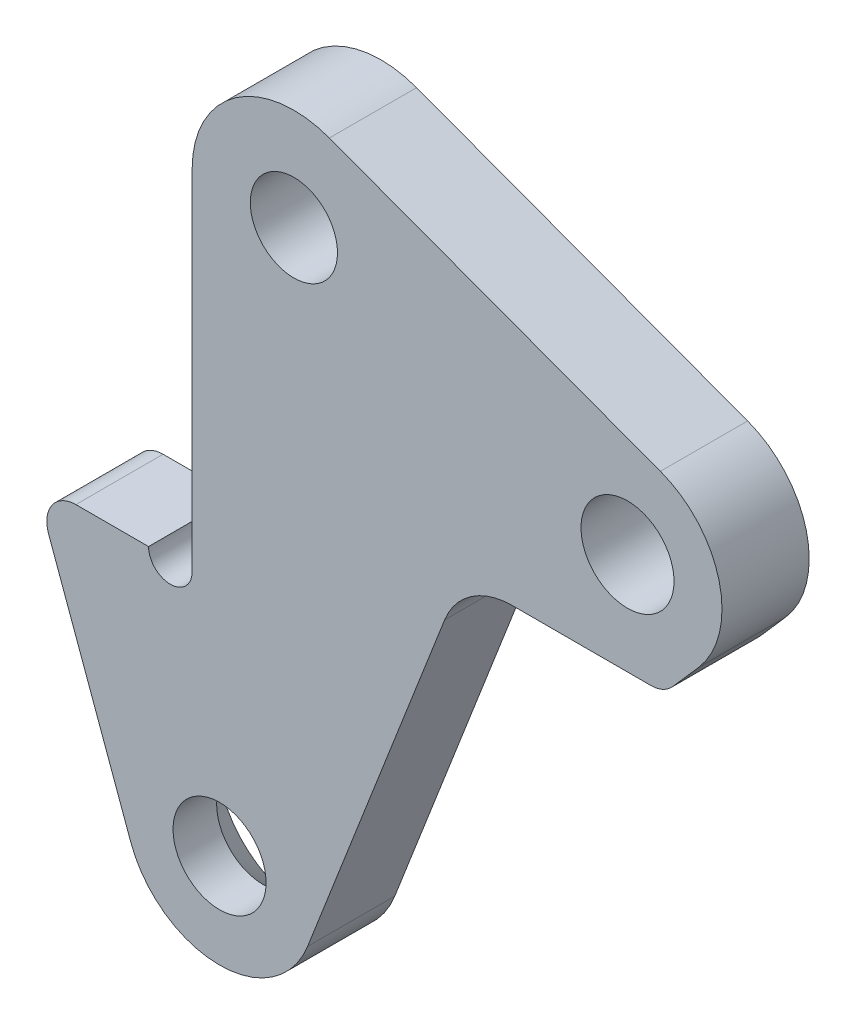
SolidWorks part; units mm, degrees
ref_plane "前视基准面" through (0, 0, 0) normal (0, 0, 1) x (1, 0, 0)
ref_plane "上视基准面" through (0, 0, 0) normal (0, 1, 0) x (1, 0, 0)
ref_plane "右视基准面" through (0, 0, 0) normal (1, 0, 0) x (0, 0, -1)
sketch "草图1" plane through (0, 0, 0) normal (0, 0, 1) x (1, 0, 0)
  line L0 (-7.5, -12) -> (-3.5, -12)
  line L1 (-3.5, -12) -> (-3.5, 0)
  line L2 (-8.4397, -13.342) -> (-5.6118, -21.1116)
  line L3 (1.2196, 3.2806) -> (12.6097, -0.9537)
  line L4 (-0.1146, -22.1432) -> (13.9204, -6.1432)
  line L5 (-8.4373, -12.6515) -> (-3.2806, 1.2196) construction
  circle A0 centre (0, 0) radius 1.5
  arc A1 (-5.6118, -21.1116) -> (-0.1146, -22.1432) centre (-2.5578, -20) ccw
  circle A2 centre (-2.5578, -20) radius 1.6
  arc A3 (-7.5, -12) -> (-8.4397, -13.342) centre (-7.5, -13) ccw
  arc A4 (-3.5, 0) -> (1.2196, 3.2806) centre (0, 0) cw
  circle A5 centre (11.4772, -4) radius 1.6
  arc A6 (13.9204, -6.1432) -> (12.6097, -0.9537) centre (11.4772, -4) ccw
  point P18 (-8.9281, -12)
  dimension "D2" = 3
  dimension "D4" = 3.2
  dimension "D5" = 3.25
  dimension "D7" = 1
  dimension "D10" = 3.25
  dimension "D11" = 3.2
  dimension "D3" = 70
  dimension "D6" = 8
  dimension "D1" = 4
  dimension "D8" = 20
  dimension "D9" = 3.5
  dimension "D13" = 4
extrude "凸台-拉伸1" add sketch "草图1" along normal mid plane 3
chamfer "倒角1" distance 1.5 angle 45 1 edges at (-0.9578, -20, -1.5)
sketch "草图2" plane through (0, 0, 1.5) normal (0, 0, 1) x (1, 0, 0)
  line L0 (-3.5, -12) -> (-7.5, -12) construction
  circle A0 centre (-4.25, -12) radius 0.75
  dimension "D1" = 1.5
extrude "切除-拉伸1" cut sketch "草图2" against normal through all
sketch "草图3" plane through (0, 0, 1.5) normal (0, 0, 1) x (1, 0, 0)
  line L0 (5.8074, -7.5) -> (12.7302, -7.5)
  line L1 (-0.1146, -22.1432) -> (13.9204, -6.1432) construction
  line L2 (12.7302, -7.5) -> (-0.1146, -22.1432)
  line L3 (0.4699, -21.1812) -> (5.8074, -7.5)
  line L4 (11.4772, -10) -> (11.4772, -4) construction
  line L5 (12.6097, -0.9537) -> (1.2196, 3.2806) construction
  circle A0 centre (11.4772, -4) radius 1.6 construction
  circle A1 centre (0, 0) radius 15.2225 construction
  circle A2 centre (11.4772, -10) radius 2.5 construction
  circle A3 centre (7.2733, -13.3725) radius 2.5 construction
  arc A4 (-5.6118, -21.1116) -> (-0.1146, -22.1432) centre (-2.5578, -20) ccw construction
  arc A5 (-0.1146, -22.1432) -> (0.4699, -21.1812) centre (-2.5578, -20) ccw
  dimension "D2" = 5
  dimension "D4" = 20.393
  dimension "D5" = 3.5
  dimension "D1" = 6
  dimension "D3" = 20.393
extrude "切除-拉伸2" cut sketch "草图3" against normal through all
fillet "圆角1" radius 2.5 1 edges at (5.8074, -7.5, 0)
fillet "圆角2" radius 1 1 edges at (12.7302, -7.5, 0)
equation "\"D1@草图1\"=5-\"D7@草图1\""
equation "\"D3@草图3\"=\"D4@草图3\""
